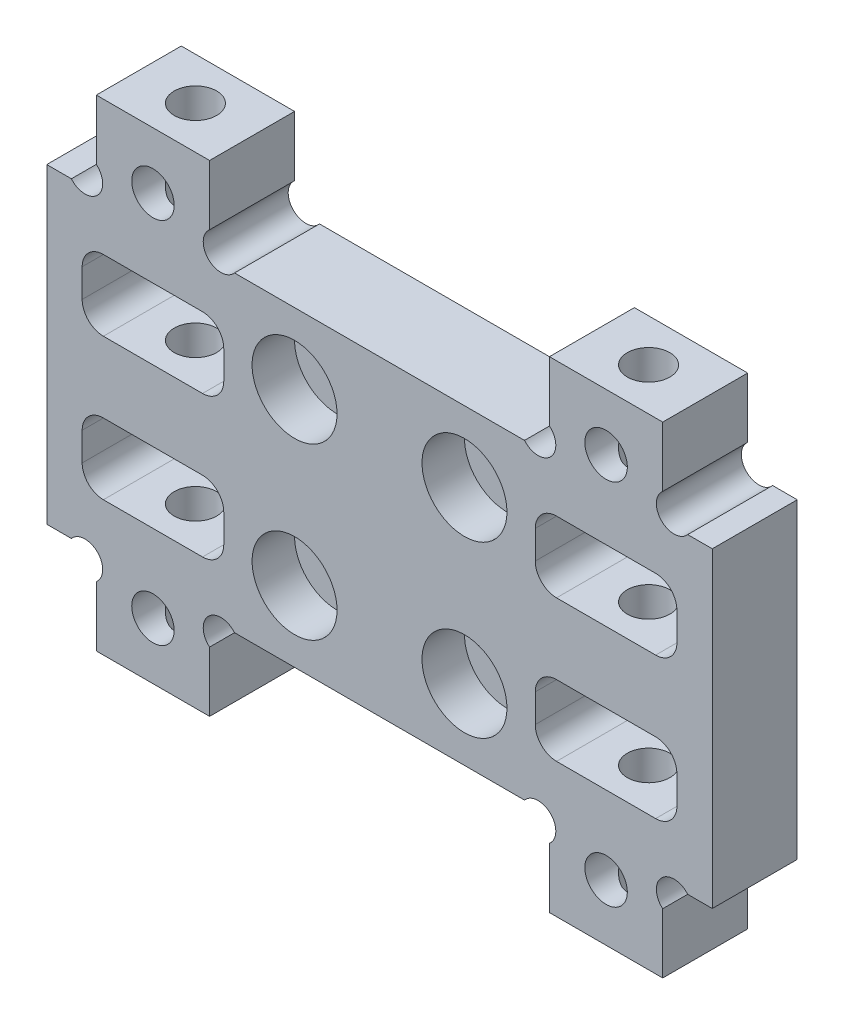
SolidWorks part; units mm, degrees
ref_plane "前视基准面" through (0, 0, 0) normal (0, 0, 1) x (1, 0, 0)
ref_plane "上视基准面" through (0, 0, 0) normal (0, 1, 0) x (1, 0, 0)
ref_plane "右视基准面" through (0, 0, 0) normal (1, 0, 0) x (0, 0, -1)
sketch "草图1" plane through (0, 0, 0) normal (0, 0, 1) x (1, 0, 0)
  line L0 (-32.1563, 0) -> (23.3992, 0) construction
  line L1 (0, 33.1916) -> (0, -32.9195) construction
  line L2 (-23.5, 11) -> (-20, 11)
  line L3 (-20, 11) -> (-20, 17)
  line L4 (-20, 17) -> (-12, 17)
  line L5 (-12, 17) -> (-12, 11)
  line L6 (-12, 11) -> (12, 11)
  line L7 (-23.5, 11) -> (-23.5, -11)
  line L8 (-16, 17) -> (-16, -17) construction
  line L9 (-12, -11) -> (12, -11)
  line L10 (-12, -17) -> (-12, -11)
  line L11 (-20, -17) -> (-12, -17)
  line L12 (-20, -11) -> (-20, -17)
  line L13 (-23.5, -11) -> (-20, -11)
  line L14 (16, 17) -> (16, -17) construction
  line L15 (23.5, -11) -> (20, -11)
  line L16 (20, -11) -> (20, -17)
  line L17 (20, -17) -> (12, -17)
  line L18 (12, -17) -> (12, -11)
  line L19 (23.5, 11) -> (23.5, -11)
  line L20 (12, 17) -> (12, 11)
  line L21 (20, 17) -> (12, 17)
  line L22 (20, 11) -> (20, 17)
  line L23 (23.5, 11) -> (20, 11)
  point P18 (-16, 0)
  point P19 (-23.5, 0)
  point P29 (0, -11)
  point P31 (0, 11)
  point P34 (23.5, 0)
  point P35 (16, 0)
  dimension "D1" = 6
  dimension "D2" = 16
  dimension "D3" = 8
  dimension "D4" = 3.5
  dimension "D5" = 17
extrude "凸台-拉伸1" add sketch "草图1" along normal blind 6
sketch "草图3" plane through (0, 11, 0) normal (0, 1, 0) x (1, 0, 0)
  line L0 (0, -9.9485) -> (0, 7.0989) construction
  circle A0 centre (16, -3) radius 1.5
  circle A1 centre (-7, -3) radius 1.5 construction
  circle A2 centre (-16, -3) radius 1.5
  circle A3 centre (7, -3) radius 1.5 construction
  circle A4 centre (16, -3) radius 1.5 construction
  circle A5 centre (-16, -3) radius 1.5 construction
  dimension "D1" = 32
  dimension "D2" = 3
extrude "切除-拉伸1" cut sketch "草图3" against normal through all and the other way blind 10
sketch "草图4" plane through (0, 0, 0) normal (0, 0, -1) x (-1, 0, 0)
  line L0 (0, -21.5156) -> (0, 23.5402) construction
  line L1 (23.5, 0) -> (-23.5, 0) construction
  line L2 (23.5, 11) -> (23.5, -11) construction
  line L3 (-23.5, -11) -> (-23.5, 11) construction
  line L4 (17.5, 17) -> (14.5, 17) construction
  line L5 (8.5, 16) -> (5.5, 16) construction
  line L6 (16, 17) -> (16, -11) construction
  line L8 (11, 7.5) -> (11, 2.5)
  line L9 (21, -7.5) -> (11, -7.5)
  line L10 (21, -7.5) -> (21, -2.5)
  line L11 (21, -2.5) -> (11, -2.5)
  line L12 (11, -7.5) -> (11, -2.5)
  line L13 (21, -7.5) -> (11, -2.5) construction
  line L14 (21, -2.5) -> (11, -7.5) construction
  line L15 (21, 2.5) -> (11, 2.5)
  line L16 (21, 7.5) -> (21, 2.5)
  line L17 (21, 7.5) -> (11, 7.5)
  line L18 (-21, -2.5) -> (-11, -7.5) construction
  line L19 (-21, -7.5) -> (-11, -2.5) construction
  line L20 (-21, 7.5) -> (-11, 7.5)
  line L21 (-21, 7.5) -> (-21, 2.5)
  line L22 (-21, 2.5) -> (-11, 2.5)
  line L23 (-11, -7.5) -> (-11, -2.5)
  line L24 (-21, -2.5) -> (-11, -2.5)
  line L25 (-21, -7.5) -> (-21, -2.5)
  line L26 (-21, -7.5) -> (-11, -7.5)
  line L27 (-11, 7.5) -> (-11, 2.5)
  line L29 (17.5, 17) -> (14.5, 17) construction
  line L30 (21, -2.5) -> (11, -2.5) construction
  line L31 (21, -2.5) -> (21, 2.5) construction
  line L32 (21, 2.5) -> (11, 2.5) construction
  line L33 (11, -2.5) -> (11, 2.5) construction
  line L34 (21, -2.5) -> (11, 2.5) construction
  line L35 (21, 2.5) -> (11, -2.5) construction
  line L36 (-21, 2.5) -> (-11, -2.5) construction
  line L37 (-21, -2.5) -> (-11, 2.5) construction
  line L38 (-11, -2.5) -> (-11, 2.5) construction
  line L39 (-21, 2.5) -> (-11, 2.5) construction
  line L40 (-21, -2.5) -> (-21, 2.5) construction
  line L41 (-21, -2.5) -> (-11, -2.5) construction
  point P13 (16, 0)
  point P15 (16, -5)
  point P32 (-16, -5)
  point P42 (-16, 0)
  dimension "D1" = 10
  dimension "D2" = 5
  dimension "D3" = 5
  dimension "D4" = 5
  dimension "D5" = 16
  dimension "D6" = 10
extrude "切除-拉伸2" cut sketch "草图4" against normal through all
sketch "草图5" plane through (0, 0, 0) normal (0, 0, -1) x (-1, 0, 0)
  line L0 (-23.5, 0) -> (23.5, 0) construction
  line L1 (-23.5, -11) -> (-23.5, 11) construction
  line L2 (23.5, 11) -> (23.5, -11) construction
  line L3 (-20, 17) -> (-12, 17) construction
  line L4 (0, 0) -> (0, 11) construction
  line L5 (-12, 11) -> (12, 11) construction
  circle A1 centre (-16, 13) radius 1.5
  circle A3 centre (16, 13) radius 1.5
  circle A4 centre (16, -13) radius 1.5
  circle A5 centre (-16, -13) radius 1.5
  point P5 (-16, 17)
  dimension "D1" = 3
  dimension "D2" = 4
extrude "切除-拉伸3" cut sketch "草图5" against normal through all
sketch "草图6" plane through (0, 0, 6) normal (0, 0, 1) x (1, 0, 0)
  circle A0 centre (-20, 11) radius 1
  circle A1 centre (-12, 11) radius 1
  circle A2 centre (12, 11) radius 1
  circle A3 centre (20, 11) radius 1
  circle A4 centre (-20, -11) radius 1
  circle A5 centre (-12, -11) radius 1
  circle A6 centre (12, -11) radius 1
  circle A7 centre (20, -11) radius 1
  dimension "D1" = 2
extrude "切除-拉伸4" [suppressed] cut sketch "草图6" against normal through all
fillet "圆角2" [suppressed] radius 1.5
sketch "草图7" plane through (0, 0, 6) normal (0, 0, 1) x (1, 0, 0)
  line L0 (-20, 11) -> (-23.5, 11) construction
  line L1 (-20, 17) -> (-20, 11) construction
  line L2 (-12, 11) -> (-12, 17) construction
  line L3 (12, 17) -> (12, 11) construction
  line L4 (20, 11) -> (20, 17) construction
  line L5 (-27.6963, 0) -> (27.2152, 0) construction
  circle A0 centre (-20, 10) radius 1.5
  circle A1 centre (-12, 10) radius 1.5
  circle A2 centre (12, 10) radius 1.5
  circle A3 centre (20, 10) radius 1.5
  circle A4 centre (20, -10) radius 1.5
  circle A5 centre (12, -10) radius 1.5
  circle A6 centre (-12, -10) radius 1.5
  circle A7 centre (-20, -10) radius 1.5
  dimension "D1" = 3
  dimension "D2" = 1
extrude "切除-拉伸5" [suppressed] cut sketch "草图7" against normal through all
sketch "草图8" plane through (0, 0, 6) normal (0, 0, 1) x (1, 0, 0)
  line L1 (5.5, -7.5) -> (-5.5, -7.5)
  line L2 (5.5, -7.5) -> (5.5, 7.5)
  line L3 (5.5, 7.5) -> (-5.5, 7.5)
  line L4 (-5.5, -7.5) -> (-5.5, 7.5)
  line L5 (5.5, -7.5) -> (-5.5, 7.5) construction
  line L6 (5.5, 7.5) -> (-5.5, -7.5) construction
  point P0 (0, 0)
  dimension "D1" = 11
  dimension "D2" = 15
extrude "切除-拉伸6" [suppressed] cut sketch "草图8" against normal through all
fillet "圆角3" [suppressed] radius 2
fillet "圆角4" radius 1.5 16 edges at (-21, 2.5, 3) (-11, 2.5, 3) (-11, 7.5, 3) (-21, 7.5, 3) (11, -7.5, 3) (21, -7.5, 3) (21, -2.5, 3) (11, -2.5, 3) (11, 2.5, 3) (21, 2.5, 3) (21, 7.5, 3) (11, 7.5, 3) (-21, -2.5, 3) (-11, -2.5, 3) (-11, -7.5, 3) (-21, -7.5, 3)
sketch "草图9" plane through (0, 0, 0) normal (0, 0, -1) x (-1, 0, 0)
  line L0 (-12, 11) -> (12, 11) construction
  line L1 (-12, 17) -> (-12, 11) construction
  line L2 (0, 0) -> (0, 20.5067) construction
  line L3 (0, 0) -> (-23.5, 0) construction
  line L4 (-23.5, -11) -> (-23.5, 11) construction
  line L5 (-16, 17) -> (-16, 8.4017) construction
  line L6 (-20, 17) -> (-12, 17) construction
  circle A0 centre (-11.2, 11.8) radius 1.25
  circle A1 centre (11.2, 11.8) radius 1.25
  circle A2 centre (11.2, -11.8) radius 1.25
  circle A3 centre (-11.2, -11.8) radius 1.25
  circle A4 centre (-20.8, 11.8) radius 1.25
  circle A5 centre (20.8, 11.8) radius 1.25
  circle A6 centre (20.8, -11.8) radius 1.25
  circle A7 centre (-20.8, -11.8) radius 1.25
  dimension "D1" = 2.5
  dimension "D2" = 0.8
  dimension "D3" = 0.8
extrude "切除-拉伸7" cut sketch "草图9" against normal through all
sketch "草图11" plane through (0, 0, 0) normal (0, 0, -1) x (-1, 0, 0)
  line L0 (6, 11) -> (6, -11) construction
  line L1 (-10.2395, 11) -> (10.2395, 11) construction
  line L2 (10.2395, -11) -> (-10.2395, -11) construction
  line L4 (0, 0) -> (0, 18.4071) construction
  circle A0 centre (6, 6) radius 1.25
  circle A1 centre (6, -6) radius 1.25
  circle A2 centre (-6, 6) radius 1.25
  circle A3 centre (-6, -6) radius 1.25
  dimension "D1" = 2.5
  dimension "D2" = 2.5
  dimension "D3" = 5
  dimension "D4" = 5
  dimension "D5" = 6
extrude "切除-拉伸9" cut sketch "草图11" against normal through all
sketch "草图12" plane through (0, 0, 6) normal (0, 0, 1) x (1, 0, 0)
  circle A0 centre (-6, 6) radius 3
  circle A1 centre (-6, -6) radius 3
  circle A2 centre (6, 6) radius 3
  circle A3 centre (6, -6) radius 3
  dimension "D1" = 6
  dimension "D2" = 6
  dimension "D3" = 6
  dimension "D4" = 6
extrude "切除-拉伸10" cut sketch "草图12" against normal blind 3
